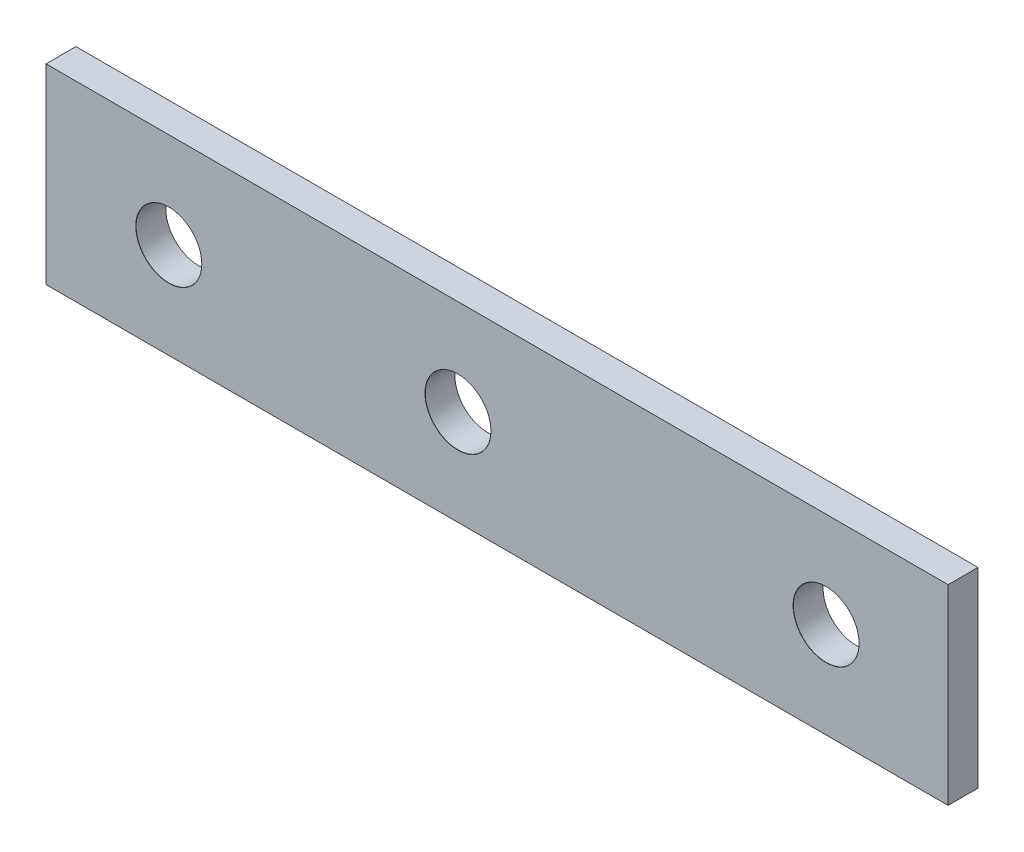
SolidWorks part; units mm, degrees
ref_plane "Front Plane" through (0, 0, 0) normal (0, 0, 1) x (1, 0, 0)
ref_plane "Top Plane" through (0, 0, 0) normal (0, 1, 0) x (1, 0, 0)
ref_plane "Right Plane" through (0, 0, 0) normal (1, 0, 0) x (0, 0, -1)
sketch "Esquisse1" plane through (0, 0, 0) normal (0, 0, 1) x (1, 0, 0)
  line L1 (0, 0) -> (151, 0)
  line L2 (0, 0) -> (0, 32)
  line L3 (0, 32) -> (151, 32)
  line L4 (151, 0) -> (151, 32)
  dimension "D1" = 151
  dimension "D2" = 32
extrude "Boss.-Extru.1" add sketch "Esquisse1" along normal blind 5
sketch "Esquisse2" plane through (0, 0, 5) normal (0, 0, 1) x (1, 0, 0)
  line L0 (0, 16) -> (151, 16) construction
  line L1 (0, 32) -> (0, 0) construction
  line L2 (151, 0) -> (151, 32) construction
  line L3 (20.5, 32) -> (20.5, 0) construction
  line L4 (151, 32) -> (0, 32) construction
  line L5 (0, 0) -> (151, 0) construction
  line L6 (69, 32) -> (69, 0) construction
  line L7 (130.5, 32) -> (130.5, 0) construction
  dimension "D1" = 20.5
  dimension "D2" = 48.5
  dimension "D3" = 20.5
hole_wizard "Dégagement M101" positions "Esquisse3D1" profile "Esquisse3" hole size "M10" standard "Ansi Metric"
sketch3d "Esquisse3D1"
  line L0 (0, 16, 5) -> (151, 16, 5) construction
  point P0 (20.5525, 16, 5)
  point P4 (68.9513, 16, 5)
  point P5 (130.5712, 16, 5)
sketch "Esquisse3" plane through (20.5525, 16, 5) normal (1, 0, 0) x (0, -1, 0)
  line L0 (0, 0) -> (0, 40.3047)
  line L1 (0, 40.3047) -> (5.5, 37)
  line L2 (5.5, 37) -> (5.5, 0.025)
  line L3 (5.5, 0.025) -> (5.525, 0)
  line L5 (5.525, 0) -> (0, 0)
  line L6 (-5.5, 0.025) -> (-5.525, 0) construction
  line L10 (0, 40.3047) -> (-5.5, 37) construction
  line L11 (0, -6.35) -> (0, 107.95) construction
  dimension "Diamètre du perçage" = 11
  dimension "Profondeur du perçage" = 37
  dimension "Diamètre du fraisage entrant" = 11.05
  dimension "Angle du fraisage entrant" = 90
  dimension "Angle de pointe" = 118
